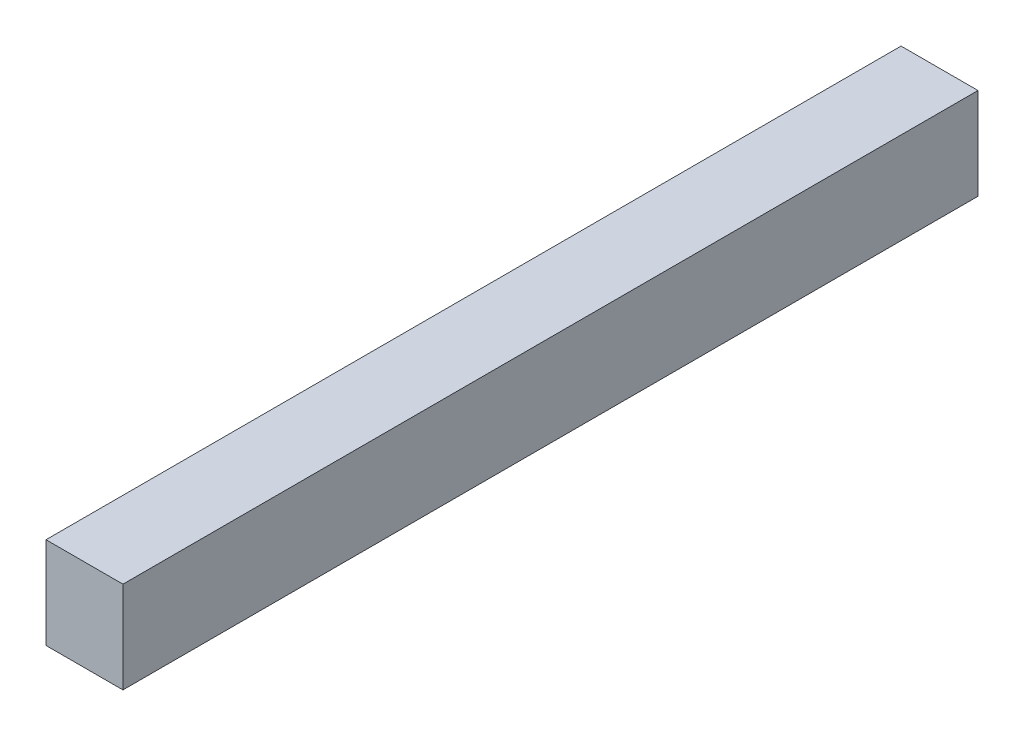
SolidWorks part; units mm, degrees
ref_plane "Front" through (0, 0, 0) normal (0, 0, 1) x (1, 0, 0)
ref_plane "Top" through (0, 0, 0) normal (0, 1, 0) x (1, 0, 0)
ref_plane "Right" through (0, 0, 0) normal (1, 0, 0) x (0, 0, -1)
sketch "Esquisse1" plane through (0, 0, 0) normal (0, 0, 1) x (1, 0, 0)
  line L1 (0, 0) -> (63, 0)
  line L2 (0, 0) -> (0, 75)
  line L3 (0, 75) -> (63, 75)
  line L4 (63, 0) -> (63, 75)
  dimension "D1" = 63
  dimension "D2" = 75
extrude "Boss.-Extru.1" add sketch "Esquisse1" along normal blind 700
